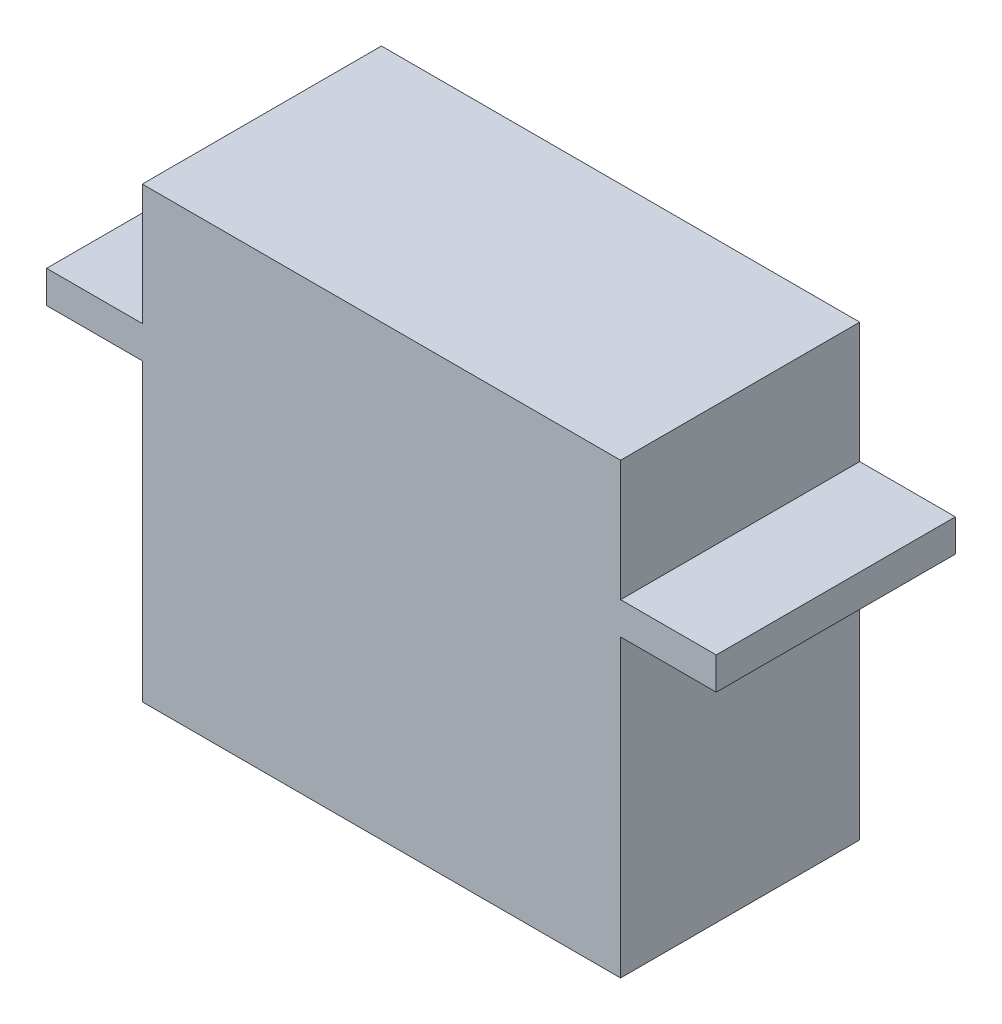
SolidWorks part; units mm, degrees
ref_plane "Front Plane" through (0, 0, 0) normal (0, 0, 1) x (1, 0, 0)
ref_plane "Top Plane" through (0, 0, 0) normal (0, 1, 0) x (1, 0, 0)
ref_plane "Right Plane" through (0, 0, 0) normal (1, 0, 0) x (0, 0, -1)
sketch "Sketch1" plane through (0, 0, 0) normal (0, 0, 1) x (1, 0, 0)
  line L0 (0, 24.7) -> (56, 24.7)
  line L1 (0, 0) -> (56, 0)
  line L2 (0, 0) -> (0, 37.5)
  line L3 (0, 37.5) -> (56, 37.5)
  line L4 (56, 0) -> (56, 37.5)
  line L5 (8.1538, 37.5) -> (48.1538, 37.5)
  line L6 (8.1538, 37.5) -> (8.1538, 0)
  line L7 (8.1538, 0) -> (48.1538, 0)
  line L8 (48.1538, 37.5) -> (48.1538, 0)
  dimension "D2" = 56
  dimension "D3" = 40
  dimension "D4" = 37.5
  dimension "D5" = 24.7
extrude "Boss-Extrude1" add sketch "Sketch1" along normal blind 20 contours L6 L3 L2 L0 | L6 L0 L2 L1 | L8 L3 L6 L0 | L8 L0 L6 L1 | L3 L8 L0 L4 | L0 L8 L1 L4
sketch "Sketch4" plane through (0, 0, 0) normal (-1, 0, 0) x (0, 0, 1)
  line L0 (0, 0) -> (0, 37.5) construction
  line L1 (0, 24.7) -> (20, 24.7)
  line L2 (0, 24.7) -> (0, 0)
  line L3 (0, 0) -> (20, 0)
  line L4 (20, 24.7) -> (20, 0)
  dimension "D1" = 24.7
extrude "Cut-Extrude1" cut sketch "Sketch4" against normal blind 8
sketch "Sketch5" plane through (56, 0, 0) normal (1, 0, 0) x (0, 0, -1)
  line L0 (-20, 0) -> (-20, 37.5) construction
  line L1 (-20, 24.7) -> (0, 24.7)
  line L2 (-20, 24.7) -> (-20, 0)
  line L3 (-20, 0) -> (0, 0)
  line L4 (0, 24.7) -> (0, 0)
  dimension "D1" = 24.7
extrude "Cut-Extrude2" cut sketch "Sketch5" against normal blind 8
sketch "Sketch6" plane through (56, 0, 0) normal (1, 0, 0) x (0, 0, -1)
  line L0 (0, 24.7) -> (0, 37.5) construction
  line L1 (-20, 24.7) -> (0, 24.7)
  line L2 (-20, 24.7) -> (-20, 27.4)
  line L3 (-20, 27.4) -> (0, 27.4)
  line L4 (0, 24.7) -> (0, 27.4)
  line L6 (-20, 37.5) -> (0, 37.5)
  line L7 (-20, 37.5) -> (-20, 27.4)
  line L8 (-20, 27.4) -> (0, 27.4)
  line L9 (0, 37.5) -> (0, 27.4)
  dimension "D1" = 2.7
extrude "Cut-Extrude3" cut sketch "Sketch6" against normal blind 8 contours L7 L6 L9 L8
sketch "Sketch7" plane through (0, 0, 0) normal (-1, 0, 0) x (0, 0, 1)
  line L0 (20, 24.7) -> (20, 37.5) construction
  line L1 (0, 24.7) -> (20, 24.7)
  line L2 (0, 24.7) -> (0, 27.4)
  line L3 (0, 27.4) -> (20, 27.4)
  line L4 (20, 24.7) -> (20, 27.4)
  line L6 (0, 37.5) -> (20, 37.5)
  line L7 (0, 37.5) -> (0, 27.4)
  line L8 (0, 27.4) -> (20, 27.4)
  line L9 (20, 37.5) -> (20, 27.4)
  dimension "D1" = 2.7
extrude "Cut-Extrude4" cut sketch "Sketch7" against normal blind 8 contours L7 L6 L9 L8
